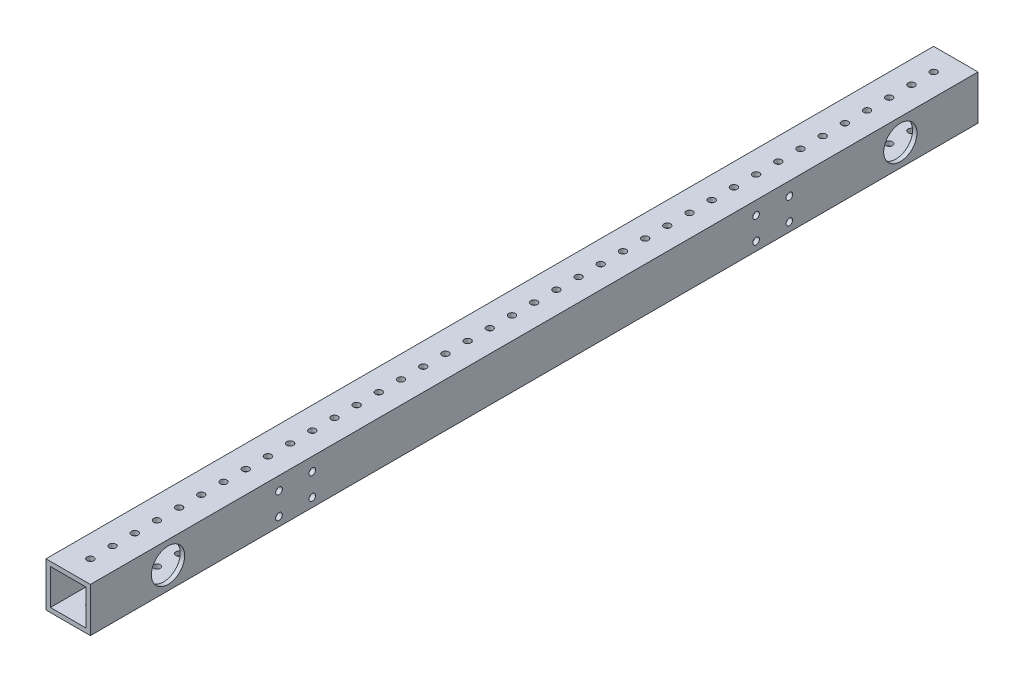
SolidWorks part; units mm, degrees
ref_plane "前视基准面" through (0, 0, 0) normal (0, 0, 1) x (1, 0, 0)
ref_plane "上视基准面" through (0, 0, 0) normal (0, 1, 0) x (1, 0, 0)
ref_plane "右视基准面" through (0, 0, 0) normal (1, 0, 0) x (0, 0, -1)
sketch "草图1" plane through (0, 0, 0) normal (0, 0, 1) x (1, 0, 0)
  line L1 (0, 20) -> (20, 20)
  line L2 (0, 20) -> (0, 0)
  line L3 (0, 0) -> (20, 0)
  line L4 (20, 20) -> (20, 0)
  line L5 (2, 18) -> (18, 18)
  line L6 (2, 18) -> (2, 2)
  line L7 (2, 2) -> (18, 2)
  line L8 (18, 18) -> (18, 2)
  dimension "D1" = 20
  dimension "D2" = 20
  dimension "D3" = 2
  dimension "D4" = 2
  dimension "D5" = 2
  dimension "D6" = 2
extrude "凸台-拉伸1" add sketch "草图1" along normal blind 400
sketch "草图4" plane through (0, 0, 0) normal (-1, 0, 0) x (0, 0, 1)
  line L0 (0, 10) -> (753.1431, 10) construction
  line L1 (0, 20) -> (0, 0) construction
  line L2 (200, -10.7051) -> (200, 94.4528) construction
  line L3 (10, 0) -> (40, 0) construction
  line L4 (40, 0) -> (70, 0) construction
  line L5 (40, 20) -> (70, 20) construction
  line L6 (10, 20) -> (40, 20) construction
  line L7 (390, 20) -> (360, 20) construction
  line L8 (360, 20) -> (330, 20) construction
  line L9 (360, 0) -> (330, 0) construction
  line L10 (390, 0) -> (360, 0) construction
  line L11 (400, 0) -> (0, 0) construction
  line L13 (149.95, 17.05) -> (149.95, -19.8914)
  line L14 (149.95, -19.8914) -> (179.95, -19.8914)
  line L15 (179.95, 17.05) -> (179.95, -19.8914)
  line L20 (400, 20) -> (400, 0) construction
  line L21 (149.95, 20.05) -> (179.95, 20.05)
  line L22 (250.05, 20.05) -> (220.05, 20.05)
  line L23 (220.05, 17.05) -> (220.05, -19.8914)
  line L24 (250.05, -19.8914) -> (220.05, -19.8914)
  line L25 (250.05, 17.05) -> (250.05, -19.8914)
  circle A0 centre (10, 0) radius 1.5
  circle A1 centre (40, 0) radius 1.5
  circle A2 centre (70, 0) radius 1.5
  circle A3 centre (70, 20) radius 1.5
  circle A4 centre (40, 20) radius 1.5
  circle A5 centre (10, 20) radius 1.5
  circle A6 centre (390, 20) radius 1.5
  circle A7 centre (360, 20) radius 1.5
  circle A8 centre (330, 20) radius 1.5
  circle A9 centre (330, 0) radius 1.5
  circle A10 centre (360, 0) radius 1.5
  circle A11 centre (390, 0) radius 1.5
  arc A12 (149.95, 17.05) -> (149.95, 20.05) centre (149.95, 18.55) cw
  arc A13 (179.95, 20.05) -> (179.95, 17.05) centre (179.95, 18.55) cw
  arc A14 (220.05, 20.05) -> (220.05, 17.05) centre (220.05, 18.55) ccw
  arc A15 (250.05, 17.05) -> (250.05, 20.05) centre (250.05, 18.55) ccw
  dimension "D1" = 3
  dimension "D2" = 3
  dimension "D3" = 3
  dimension "D10" = 1.5
  dimension "D13" = 1.5
  dimension "D4" = 30
  dimension "D5" = 30
  dimension "D6" = 10
  dimension "D7" = 10
  dimension "D8" = 30
  dimension "D9" = 149.95
  dimension "D11" = 19.8914
  dimension "D12" = 20.05
  dimension "D14" = 17.05
extrude "切除-拉伸3" [suppressed] cut sketch "草图4" against normal through all
sketch "草图6" [suppressed] plane through (0, 40, 0) normal (0, 1, 0) x (1, 0, 0)
  line L0 (10, 52.9127) -> (10, -670.0691) construction
  line L1 (20, -580) -> (20, 0) construction
  line L2 (0, -580) -> (0, 0) construction
  line L3 (18, 30.077) -> (18, -701.2226) construction
  line L4 (2, 30.077) -> (2, -701.2226) construction
  line L5 (20, -580) -> (0, -580) construction
  line L6 (20, 0) -> (0, 0) construction
  circle A0 centre (18, -19) radius 1.5
  circle A1 centre (18, -70) radius 1.5
  circle A2 centre (18, -90) radius 1.5
  circle A3 centre (10, -130) radius 1.5
  circle A4 centre (10, -200) radius 1.5
  circle A5 centre (10, -250) radius 1.5
  circle A6 centre (10, -380) radius 1.5
  circle A7 centre (10, -450) radius 1.5
  circle A8 centre (18, -490) radius 1.5
  circle A9 centre (18, -510) radius 1.5
  circle A10 centre (18, -561) radius 1.5
  circle A11 centre (10, -270) radius 1.5
  circle A12 centre (10, -290) radius 1.5
  circle A13 centre (10, -310) radius 1.5
  circle A14 centre (10, -330) radius 1.5
  circle A15 centre (2, -561) radius 1.5
  circle A16 centre (2, -510) radius 1.5
  circle A17 centre (2, -490) radius 1.5
  circle A18 centre (10, -330) radius 1.5
  circle A19 centre (10, -310) radius 1.5
  circle A20 centre (10, -290) radius 1.5
  circle A21 centre (10, -270) radius 1.5
  circle A22 centre (10, -250) radius 1.5
  circle A23 centre (2, -90) radius 1.5
  circle A24 centre (2, -70) radius 1.5
  circle A25 centre (2, -19) radius 1.5
  dimension "D2" = 3
  dimension "D1" = 8
  dimension "D3" = 19
  dimension "D4" = 51
  dimension "D5" = 20
  dimension "D6" = 40
  dimension "D7" = 70
  dimension "D8" = 19
  dimension "D9" = 51
  dimension "D10" = 20
  dimension "D11" = 40
  dimension "D12" = 70
  dimension "D13" = 50
  dimension "D14" = 10
  dimension "D16" = 20
  dimension "D15" = 5
sketch "草图9" plane through (0, 20, 0) normal (0, 1, 0) x (1, 0, 0)
  line L0 (10, 9.6997) -> (10, -367.1122) construction
  line L1 (0, -400) -> (0, 0) construction
  line L2 (20, -400) -> (20, 0) construction
  line L3 (20, -400) -> (0, -400) construction
  circle A0 centre (10, -390) radius 1.5
  circle A1 centre (10, -380) radius 1.5
  circle A2 centre (10, -370) radius 1.5
  circle A3 centre (10, -360) radius 1.5
  circle A4 centre (10, -350) radius 1.5
  circle A5 centre (10, -340) radius 1.5
  circle A6 centre (10, -330) radius 1.5
  circle A7 centre (10, -320) radius 1.5
  circle A8 centre (10, -310) radius 1.5
  circle A9 centre (10, -300) radius 1.5
  circle A10 centre (10, -290) radius 1.5
  circle A11 centre (10, -280) radius 1.5
  circle A12 centre (10, -270) radius 1.5
  circle A13 centre (10, -260) radius 1.5
  circle A14 centre (10, -250) radius 1.5
  circle A15 centre (10, -240) radius 1.5
  circle A16 centre (10, -230) radius 1.5
  circle A17 centre (10, -220) radius 1.5
  circle A18 centre (10, -210) radius 1.5
  circle A19 centre (10, -200) radius 1.5
  circle A20 centre (10, -190) radius 1.5
  circle A21 centre (10, -180) radius 1.5
  circle A22 centre (10, -170) radius 1.5
  circle A23 centre (10, -160) radius 1.5
  circle A24 centre (10, -150) radius 1.5
  circle A25 centre (10, -140) radius 1.5
  circle A26 centre (10, -130) radius 1.5
  circle A27 centre (10, -120) radius 1.5
  circle A28 centre (10, -110) radius 1.5
  circle A29 centre (10, -100) radius 1.5
  circle A30 centre (10, -90) radius 1.5
  circle A31 centre (10, -80) radius 1.5
  circle A32 centre (10, -70) radius 1.5
  circle A33 centre (10, -60) radius 1.5
  circle A34 centre (10, -50) radius 1.5
  circle A35 centre (10, -40) radius 1.5
  circle A36 centre (10, -30) radius 1.5
  circle A37 centre (10, -20) radius 1.5
  circle A38 centre (10, -10) radius 1.5
  dimension "D1" = 3
  dimension "D2" = 10
  dimension "D4" = 10
  dimension "D3" = 39
extrude "切除-拉伸6" cut sketch "草图9" against normal through all
sketch "草图10" plane through (20, 0, 0) normal (1, 0, 0) x (0, 0, -1)
  line L0 (-400, 0) -> (-400, 20) construction
  line L1 (-400, 0) -> (0, 0) construction
  line L2 (0, 0) -> (0, 20) construction
  circle A0 centre (-365, 10) radius 7.5
  circle A1 centre (-35, 10) radius 7.5
  dimension "D2" = 15
  dimension "D4" = 15
  dimension "D1" = 35
  dimension "D3" = 10
  dimension "D5" = 10
  dimension "D6" = 35
extrude "切除-拉伸7" cut sketch "草图10" against normal through all
sketch "草图11" plane through (20, 0, 0) normal (1, 0, 0) x (0, 0, -1)
  line L0 (-400, 20) -> (0, 20) construction
  line L1 (-315, 14) -> (-300, 14) construction
  line L2 (-315, 14) -> (-315, 4) construction
  line L3 (-315, 4) -> (-300, 4) construction
  line L4 (-300, 14) -> (-300, 4) construction
  line L5 (-400, 0) -> (-400, 20) construction
  line L6 (-200, 36.2299) -> (-200, -15.5417) construction
  line L7 (0, 0) -> (0, 20) construction
  line L8 (-100, 14) -> (-100, 4) construction
  line L9 (-85, 4) -> (-100, 4) construction
  line L10 (-85, 14) -> (-85, 4) construction
  line L11 (-85, 14) -> (-100, 14) construction
  circle A0 centre (-315, 14) radius 1.5
  circle A1 centre (-300, 14) radius 1.5
  circle A2 centre (-300, 4) radius 1.5
  circle A3 centre (-315, 4) radius 1.5
  circle A4 centre (-85, 4) radius 1.5
  circle A5 centre (-100, 4) radius 1.5
  circle A6 centre (-100, 14) radius 1.5
  circle A7 centre (-85, 14) radius 1.5
  dimension "D5" = 3
  dimension "D1" = 15
  dimension "D2" = 10
  dimension "D3" = 6
  dimension "D4" = 85
extrude "切除-拉伸8" cut sketch "草图11" against normal through all
